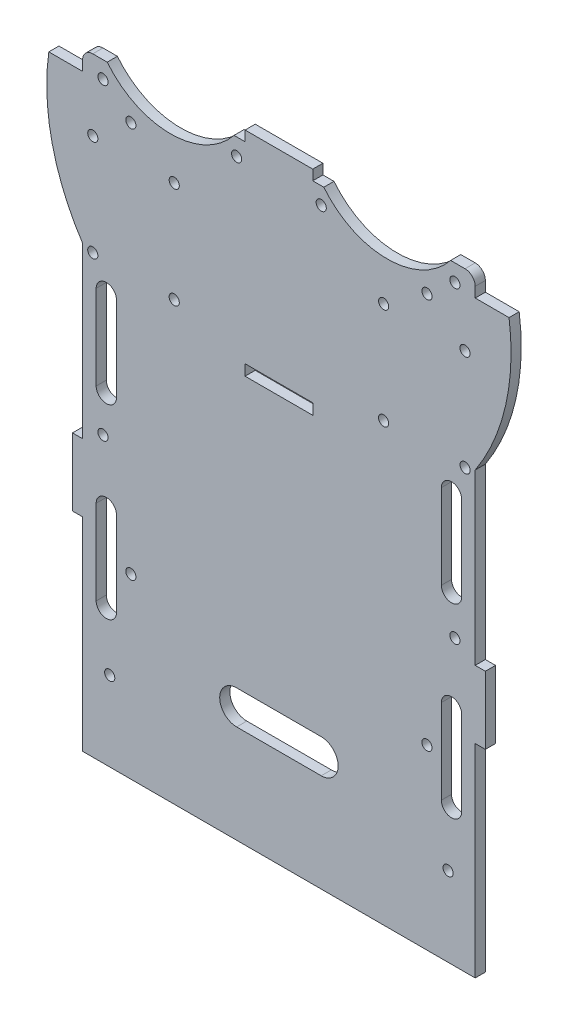
SolidWorks part; units mm, degrees
material "Maple"
ref_plane "Front Plane" through (0, 0, 0) normal (0, 0, 1) x (1, 0, 0)
ref_plane "Top Plane" through (0, 0, 0) normal (0, 1, 0) x (1, 0, 0)
ref_plane "Right Plane" through (0, 0, 0) normal (1, 0, 0) x (0, 0, -1)
sketch "Sketch1" plane through (0, 0, 0) normal (0, 0, 1) x (1, 0, 0)
  line L4 (10, 120) -> (10, 123)
  line L5 (10, 123) -> (-10, 123)
  line L6 (-10, 123) -> (-10, 120)
  line L13 (-58, 20) -> (-61, 20)
  line L18 (-61, 20) -> (-61, 0)
  line L19 (-61, 0) -> (-58, 0)
  line L24 (-58, 0) -> (-58, -60)
  line L26 (-10, 63.2) -> (10, 63.2)
  line L27 (-10, 63.2) -> (-10, 60)
  line L28 (-10, 60) -> (10, 60)
  line L29 (10, 63.2) -> (10, 60)
  line L30 (-10, 63.2) -> (10, 60) construction
  line L31 (-10, 60) -> (10, 63.2) construction
  line L32 (-58, -10) -> (0, -10) construction
  line L36 (-55, 99) -> (-30.94, 99) construction
  line L37 (55, 99) -> (30.94, 99) construction
  line L40 (-55, 99) -> (-58, 99) construction
  line L41 (55, 99) -> (58, 99) construction
  line L46 (-58, -60) -> (58, -60)
  line L47 (58, -60) -> (58, 0)
  line L48 (58, 0) -> (61, 0)
  line L49 (61, 0) -> (61, 20)
  line L50 (61, 20) -> (58, 20)
  line L51 (-58, -36.5) -> (-50, -36.5) construction
  line L52 (-50, -36.5) -> (50, -36.5) construction
  line L53 (50, -36.5) -> (58, -36.5) construction
  line L54 (0, -60) -> (0, -10) construction
  line L55 (0, -10) -> (0, 0) construction
  line L56 (0, 0) -> (0, 61.6) construction
  line L57 (0, -10) -> (58, -10) construction
  line L58 (-58, 20) -> (-58, 70)
  line L59 (58, 20) -> (58, 70)
  line L60 (-58, 117) -> (-58, 114)
  line L61 (58, 117) -> (58, 114)
  line L62 (58, 114) -> (68, 114)
  line L63 (-58, 114) -> (-68, 114)
  line L64 (-58, 115) -> (-12.5, 115) construction
  line L65 (-12.5, 115) -> (12.5, 115) construction
  line L66 (12.5, 115) -> (58, 115) construction
  line L67 (-51, 60.5) -> (-51, 35.5) construction
  line L68 (-48, 60.5) -> (-48, 35.5)
  line L69 (-54, 60.5) -> (-54, 35.5)
  line L70 (51, 60.5) -> (51, 35.5) construction
  line L71 (54, 60.5) -> (54, 35.5)
  line L72 (48, 60.5) -> (48, 35.5)
  line L73 (-58, 108) -> (-43.75, 108) construction
  line L74 (-43.75, 108) -> (43.75, 108) construction
  line L75 (43.75, 108) -> (58, 108) construction
  line L76 (-51, 5.5) -> (-51, -19.5) construction
  line L77 (-48, 5.5) -> (-48, -19.5)
  line L78 (-54, 5.5) -> (-54, -19.5)
  line L79 (51, 5.5) -> (51, -19.5) construction
  line L80 (54, 5.5) -> (54, -19.5)
  line L81 (48, 5.5) -> (48, -19.5)
  line L82 (-55, 120) -> (-50.735, 120)
  line L85 (-12.5, -26) -> (12.5, -26) construction
  line L86 (-12.5, -21) -> (12.5, -21)
  line L87 (-12.5, -31) -> (12.5, -31)
  line L88 (-58, 48) -> (-51, 48) construction
  line L89 (-51, 48) -> (51, 48) construction
  line L90 (51, 48) -> (58, 48) construction
  line L91 (-10, 120) -> (-13.265, 120)
  line L92 (10, 120) -> (13.265, 120)
  line L93 (55, 120) -> (50.735, 120)
  line L94 (-58, 24) -> (-52, 24) construction
  line L95 (-52, 24) -> (52, 24) construction
  line L96 (52, 24) -> (58, 24) construction
  circle A0 centre (-55, 99) radius 1.5
  circle A1 centre (-30.94, 99) radius 1.5
  circle A2 centre (-55, 69.11) radius 1.5
  circle A3 centre (-30.94, 69.11) radius 1.5
  circle A4 centre (30.94, 99) radius 1.5
  circle A5 centre (55, 99) radius 1.5
  circle A6 centre (30.94, 69.11) radius 1.5
  circle A7 centre (55, 69.11) radius 1.5
  arc A12 (58, 117) -> (55, 120) centre (55, 117) ccw
  arc A13 (-55, 120) -> (-58, 117) centre (-55, 117) ccw
  circle A14 centre (-50, -36.5) radius 1.5
  circle A15 centre (50, -36.5) radius 1.5
  circle A18 centre (-12.5, 115) radius 1.5
  circle A19 centre (12.5, 115) radius 1.5
  arc A20 (-48, 60.5) -> (-54, 60.5) centre (-51, 60.5) ccw
  arc A21 (-54, 35.5) -> (-48, 35.5) centre (-51, 35.5) ccw
  arc A22 (54, 60.5) -> (48, 60.5) centre (51, 60.5) ccw
  arc A23 (48, 35.5) -> (54, 35.5) centre (51, 35.5) ccw
  circle A24 centre (-43.75, 108) radius 1.5
  circle A25 centre (43.75, 108) radius 1.5
  circle A26 centre (-43.75, -7.5) radius 1.5
  circle A27 centre (43.75, -7.5) radius 1.5
  arc A28 (-48, 5.5) -> (-54, 5.5) centre (-51, 5.5) ccw
  arc A29 (-54, -19.5) -> (-48, -19.5) centre (-51, -19.5) ccw
  arc A30 (54, 5.5) -> (48, 5.5) centre (51, 5.5) ccw
  arc A31 (48, -19.5) -> (54, -19.5) centre (51, -19.5) ccw
  arc A34 (-12.5, -21) -> (-12.5, -31) centre (-12.5, -26) ccw
  arc A35 (12.5, -31) -> (12.5, -21) centre (12.5, -26) ccw
  arc A36 (-50.735, 120) -> (-13.265, 120) centre (-32, 135) ccw
  arc A37 (13.265, 120) -> (50.735, 120) centre (32, 135) ccw
  circle A38 centre (-52, 24) radius 1.5
  circle A39 centre (52, 24) radius 1.5
  circle A40 centre (-52, 115) radius 1.5
  circle A41 centre (52, 115) radius 1.5
  arc A42 (58, 70) -> (68, 114) centre (4.5978, 105.2732) ccw
  arc A43 (-58, 70) -> (-68, 114) centre (-4.5978, 105.2732) cw
  point P25 (0, 61.6)
  point P60 (-51, 48)
  point P70 (51, 48)
  point P93 (-51, -7)
  point P100 (51, -7)
  point P114 (0, -26)
  point P126 (-11.6325, 120)
  point P128 (0, 123)
  point P135 (0, 0)
  dimension "D11" = 3
  dimension "D18" = 100
  dimension "D19" = 120
  dimension "D7" = 3
  dimension "D15" = 3
  dimension "D13" = 50
  dimension "D23" = 25
  dimension "D25" = 87.5
  dimension "D29" = 3
  dimension "D35" = 32
  dimension "D5" = 24
  dimension "D36" = 5
  dimension "D37" = 104
  dimension "D39" = 44
  dimension "D40" = 64
  dimension "D2" = 20
  dimension "D3" = 3
  dimension "D4" = 20
  dimension "D6" = 50
  dimension "D8" = 60
  dimension "D9" = 3
  dimension "D10" = 29.89
  dimension "D12" = 24.06
  dimension "D14" = 3
  dimension "D16" = 23.5
  dimension "D17" = 5
  dimension "D20" = 3
  dimension "D21" = 10
  dimension "D22" = 116
  dimension "D24" = 12
  dimension "D26" = 21
  dimension "D27" = 115.5
  dimension "D28" = 25
  dimension "D30" = 15
  dimension "D31" = 102
  dimension "D32" = 53
  dimension "D33" = 108
  dimension "D34" = 34
  dimension "D38" = 91
  dimension "D41" = 3.2
extrude "Boss-Extrude1" add sketch "Sketch1" along normal blind 3
